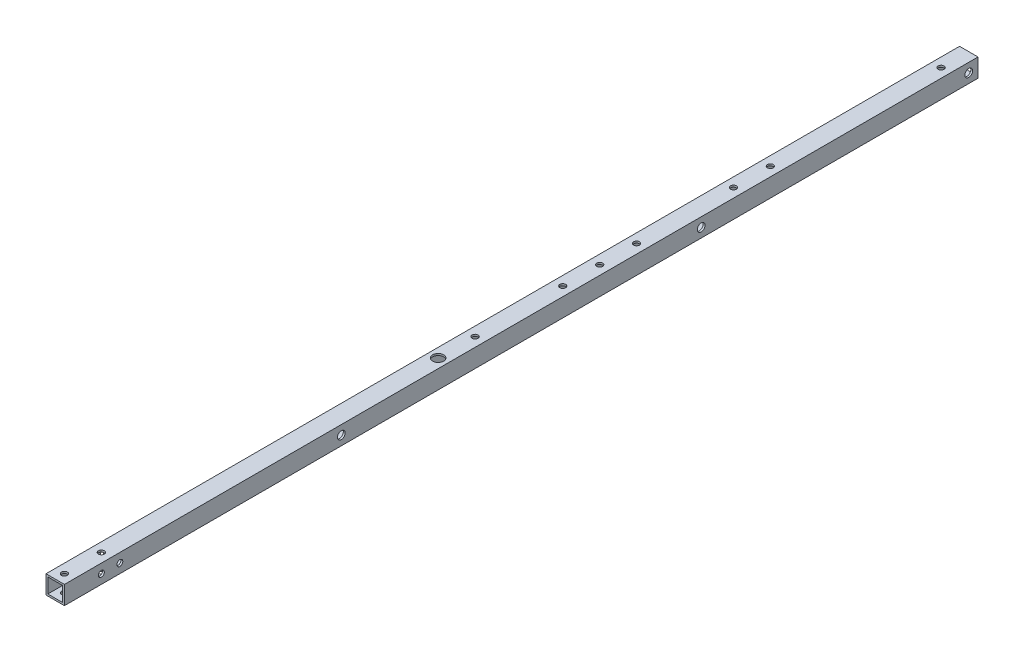
SolidWorks part; units mm, degrees
material "1060 合金"
ref_plane "正面" through (0, 0, 0) normal (0, 0, 1) x (1, 0, 0)
ref_plane "平面" through (0, 0, 0) normal (0, 1, 0) x (1, 0, 0)
ref_plane "右側面" through (0, 0, 0) normal (1, 0, 0) x (0, 0, -1)
sketch "ｽｹｯﾁ1" plane through (0, 0, 0) normal (0, 0, 1) x (1, 0, 0)
  line L1 (5, 5) -> (-5, 5)
  line L2 (5, 5) -> (5, -5)
  line L3 (5, -5) -> (-5, -5)
  line L4 (-5, 5) -> (-5, -5)
  line L5 (5, 5) -> (-5, -5) construction
  line L6 (5, -5) -> (-5, 5) construction
  point P0 (0, 0)
  dimension "D1" = 10
  dimension "D2" = 10
extrude "押し出し-薄板1" add sketch "ｽｹｯﾁ1" along normal blind 495 thin thin type one direction reverse wall 1
sketch "ｽｹｯﾁ3" plane through (5, 0, 0) normal (1, 0, 0) x (0, 0, -1)
  line L0 (0, 0) -> (-495, 0) construction
  line L1 (-495, -5) -> (-495, 5) construction
  line L2 (0, -5) -> (0, 5) construction
  circle A0 centre (-5, 0) radius 2.1
  dimension "D1" = 5
  dimension "D2" = 4.2
extrude "ｶｯﾄ - 押し出し2" cut sketch "ｽｹｯﾁ3" against normal through all
sketch "ｽｹｯﾁ2" plane through (0, 5, 0) normal (0, 1, 0) x (1, 0, 0)
  line L0 (0, 0) -> (0, -495) construction
  line L1 (5, 0) -> (-5, 0) construction
  line L2 (5, -495) -> (-5, -495) construction
  line L3 (0, -495) -> (0, -247.5) construction
  circle A0 centre (0, -15) radius 1.6
  circle A2 centre (0, -470) radius 1.6
  circle A3 centre (0, -490) radius 1.6
  circle A9 centre (0, -267.5) radius 1.6
  circle A10 centre (0, -287.5) radius 1.6
  dimension "D2" = 15
  dimension "D3" = 3.2
  dimension "D4" = 20
  dimension "D5" = 267.5
  dimension "D12" = 5
  dimension "D13" = 3.2
  dimension "D14" = 3.2
  dimension "D15" = 20
extrude "ｶｯﾄ - 押し出し1" cut sketch "ｽｹｯﾁ2" against normal through all
sketch "ｽｹｯﾁ7" plane through (5, 0, 0) normal (1, 0, 0) x (0, 0, -1)
  line L0 (-495, 0) -> (0, 0) construction
  line L1 (-495, -5) -> (-495, 5) construction
  circle A0 centre (-475, 0) radius 1.6
  circle A1 centre (-465, 0) radius 1.6
  dimension "D1" = 10
  dimension "D2" = 3.2
  dimension "D3" = 20
extrude "ｶｯﾄ - 押し出し4" cut sketch "ｽｹｯﾁ7" against normal through all
sketch "ｽｹｯﾁ9" plane through (5, 0, 0) normal (1, 0, 0) x (0, 0, -1)
  line L0 (-495, 0) -> (-247.5, 0) construction
  line L1 (-495, -5) -> (-495, 5) construction
  line L2 (-247.5, 5) -> (-247.5, -5) construction
  line L4 (-495, 5) -> (0, 5) construction
  line L5 (-495, -5) -> (0, -5) construction
  circle A8 centre (-345, 0) radius 2.1
  circle A9 centre (-150, 0) radius 2.1
  dimension "D1" = 97.5
  dimension "D4" = 4.2
extrude "ｶｯﾄ - 押し出し6" cut sketch "ｽｹｯﾁ9" against normal through all
sketch "ｽｹｯﾁ10" plane through (0, 5, 0) normal (0, 1, 0) x (1, 0, 0)
  circle A0 centre (0, -287.5) radius 3
  dimension "D1" = 6
extrude "ｶｯﾄ - 押し出し7" cut sketch "ｽｹｯﾁ10" against normal up to next
sketch "ｽｹｯﾁ11" plane through (0, -5, 0) normal (0, -1, 0) x (1, 0, 0)
  line L0 (0, 0) -> (0, 495) construction
  line L1 (-5, 495) -> (5, 495) construction
  line L2 (0, 200) -> (5, 200) construction
  line L3 (5, 495) -> (5, 0) construction
  circle A0 centre (0, 180) radius 1.6
  circle A3 centre (0, 200) radius 1.6
  circle A4 centre (0, 220) radius 1.6
  dimension "D1" = 180
  dimension "D2" = 3.2
  dimension "D3" = 20
  dimension "D4" = 3.2
extrude "ｶｯﾄ - 押し出し8" cut sketch "ｽｹｯﾁ11" against normal through all
sketch "ｽｹｯﾁ12" plane through (0, -5, 0) normal (0, -1, 0) x (1, 0, 0)
  line L0 (0, 200) -> (0, 127.5) construction
  line L1 (0, 127.5) -> (0, 107.5)
  circle A0 centre (0, 127.5) radius 1.6
  circle A3 centre (0, 107.5) radius 1.6
  dimension "D3" = 20
  dimension "D4" = 3.2
  dimension "D1" = 72.5
extrude "ｶｯﾄ - 押し出し9" cut sketch "ｽｹｯﾁ12" against normal through all contours A0 | A3
